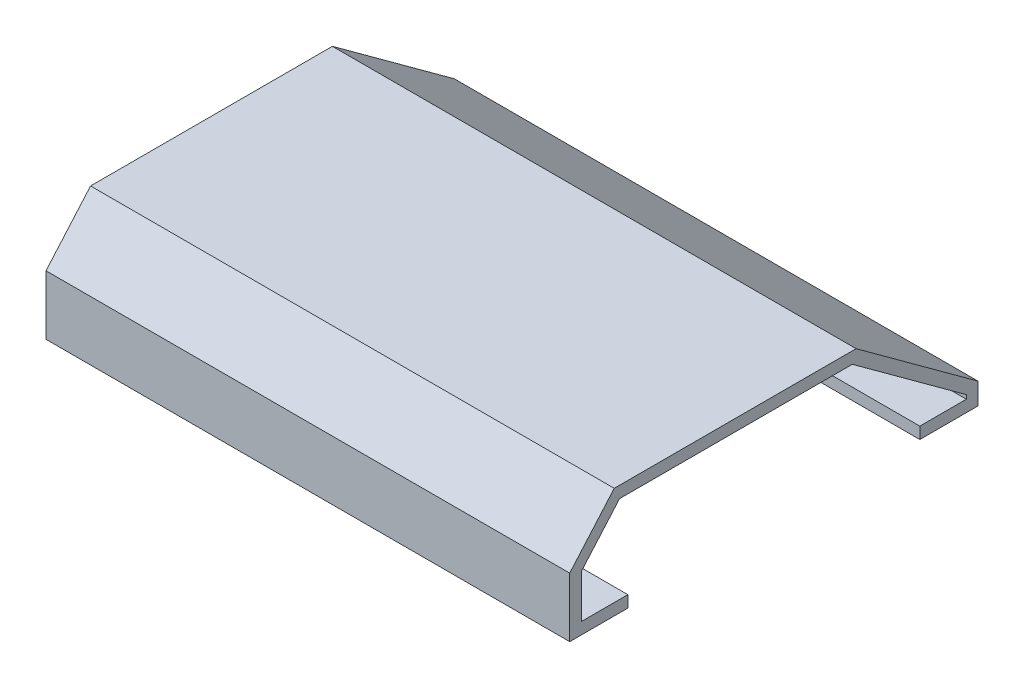
SolidWorks part; units mm, degrees
ref_plane "Front Plane" through (0, 0, 0) normal (0, 0, 1) x (1, 0, 0)
ref_plane "Top Plane" through (0, 0, 0) normal (0, 1, 0) x (1, 0, 0)
ref_plane "Right Plane" through (0, 0, 0) normal (1, 0, 0) x (0, 0, -1)
sketch "Sketch1" plane through (0, 0, 0) normal (1, 0, 0) x (0, 0, -1)
  line L0 (-26.2195, 0) -> (-34.2195, 0)
  line L1 (-34.2195, 0) -> (-34.2195, 7.4559)
  line L2 (-34.2195, 7.4559) -> (-27.6555, 15)
  line L3 (-27.6555, 15) -> (12.3445, 15)
  line L4 (12.3445, 15) -> (31.9502, 0.6801)
  line L5 (31.9502, 0.6801) -> (31.9502, 0)
  line L6 (31.9502, 0) -> (23.9502, 0)
  line L7 (-26.2195, -2) -> (-36.2195, -2)
  line L8 (-36.2195, -2) -> (-36.2195, 8.2042)
  line L9 (-36.2195, 8.2042) -> (-28.5664, 17)
  line L10 (-28.5664, 17) -> (12.9972, 17)
  line L11 (12.9972, 17) -> (33.9502, 1.696)
  line L12 (33.9502, 1.696) -> (33.9502, -2)
  line L13 (33.9502, -2) -> (23.9502, -2)
  line L14 (-26.2195, 0) -> (-26.2195, -2)
  line L15 (23.9502, 0) -> (23.9502, -2)
  dimension "D1" = 8
  dimension "D2" = 8
  dimension "D3" = 15
  dimension "D4" = 10
  dimension "D5" = 40
  dimension "D6" = 2
extrude "Boss-Extrude1" add sketch "Sketch1" along normal blind 90
sketch "Sketch2" plane through (0, 17, 0) normal (0, 1, 0) x (1, 0, 0)
  line L0 (90, -28.5664) -> (0, 12.9972) construction
  line L1 (90, 12.9972) -> (90, -28.5664) construction
  line L2 (0, 12.9972) -> (0, -28.5664) construction
  line L3 (90, 12.9972) -> (0, 12.9972) construction
  line L4 (90, 12.9972) -> (0, -28.5664) construction
  line L5 (90, -28.5664) -> (0, -28.5664) construction
  circle A0 centre (45, -7.7846) radius 6.5
  circle A1 centre (45.1069, -7.7352) radius 7.5
  dimension "D1" = 13
equation "\"D2@Sketch1\"=\"D1@Sketch1\""
equation "\"D2@Sketch3\"=\"D4@Sketch3\""
equation "\"D3@Sketch3\"=\"D1@Sketch3\""
equation "\"D7@Sketch5\"=\"D5@Sketch5\""
equation "\"D8@Sketch5\"=\"D5@Sketch5\""
